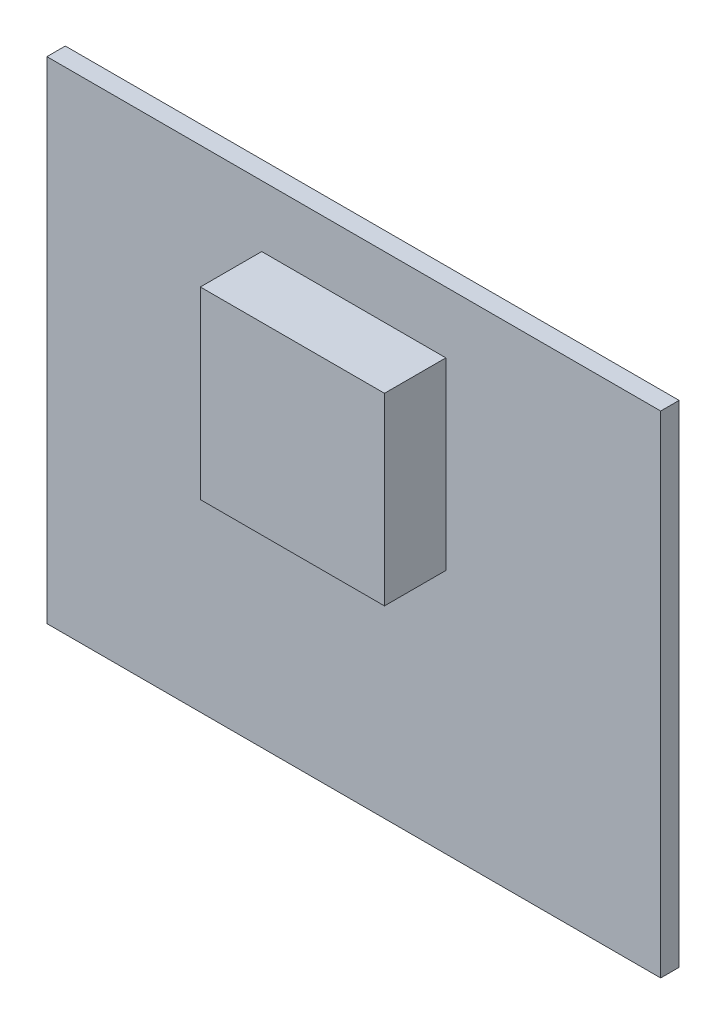
SolidWorks part; units mm, degrees
material "Du"
ref_plane "Front Plane" through (0, 0, 0) normal (0, 0, 1) x (1, 0, 0)
ref_plane "Top Plane" through (0, 0, 0) normal (0, 1, 0) x (1, 0, 0)
ref_plane "Right Plane" through (0, 0, 0) normal (1, 0, 0) x (0, 0, -1)
sketch "Sketch1" plane through (0, 0, 0) normal (0, 0, 1) x (1, 0, 0)
  line L1 (-50, 40) -> (50, 40)
  line L2 (-50, 40) -> (-50, -40)
  line L3 (-50, -40) -> (50, -40)
  line L4 (50, 40) -> (50, -40)
  line L5 (-50, 40) -> (50, -40) construction
  line L6 (-50, -40) -> (50, 40) construction
  point P0 (0, 0)
  dimension "D1" = 100
  dimension "D2" = 80
extrude "Boss-Extrude1" add sketch "Sketch1" along normal blind 3
sketch "Sketch2" plane through (0, 0, 3) normal (0, 0, 1) x (1, 0, 0)
  line L0 (50, 40) -> (-50, 40) construction
  line L1 (-15, 30) -> (15, 30)
  line L2 (-15, 30) -> (-15, 0)
  line L3 (-15, 0) -> (15, 0)
  line L4 (15, 30) -> (15, 0)
  line L5 (-15, 30) -> (15, 0) construction
  line L6 (-15, 0) -> (15, 30) construction
  line L7 (-50, 40) -> (-50, -40) construction
  point P0 (0, 15)
  dimension "D1" = 30
  dimension "D2" = 30
  dimension "D3" = 10
  dimension "D4" = 35
extrude "Boss-Extrude2" add sketch "Sketch2" along normal blind 10
